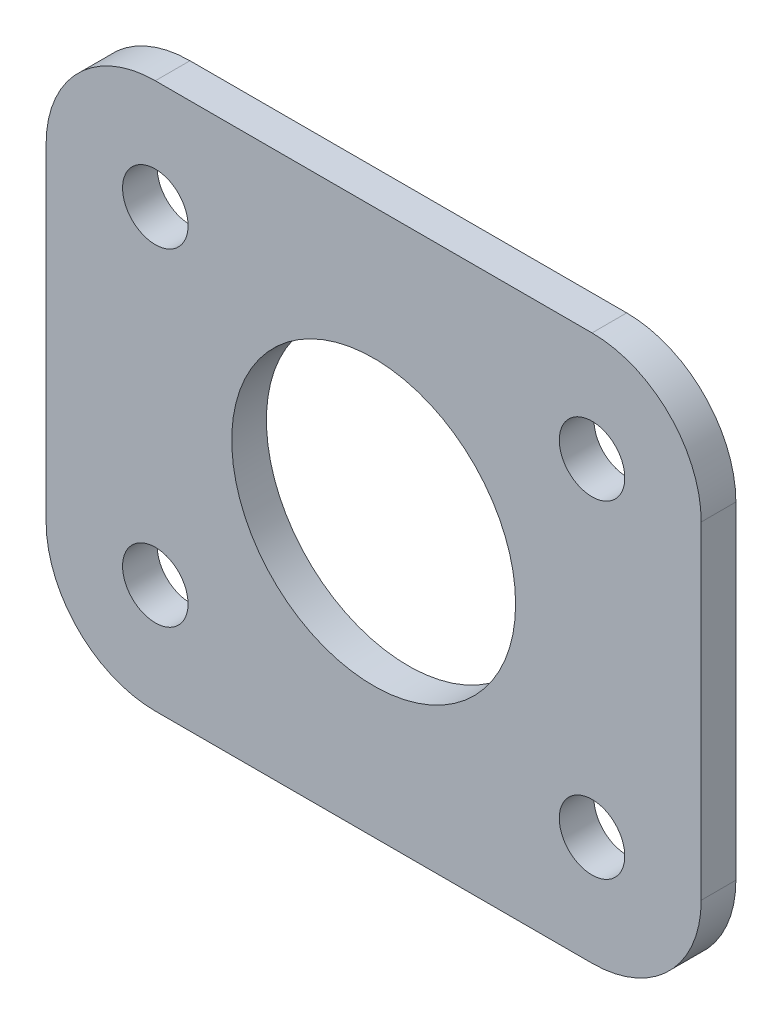
SolidWorks part; units mm, degrees
material "6061 Alloy"
ref_plane "Front Plane" through (0, 0, 0) normal (0, 0, 1) x (1, 0, 0)
ref_plane "Top Plane" through (0, 0, 0) normal (0, 1, 0) x (1, 0, 0)
ref_plane "Right Plane" through (0, 0, 0) normal (1, 0, 0) x (0, 0, -1)
sketch "Sketch1" plane through (0, 0, 0) normal (0, 0, 1) x (1, 0, 0)
  line L0 (0, 0) -> (0, 25)
  line L1 (0, 25) -> (30, 25)
  line L2 (30, 25) -> (30, 0)
  line L6 (0, 0) -> (30, 0)
  line L7 (5, 25) -> (5, 0) construction
  line L8 (0, 0) -> (5, 0) construction
  line L9 (5, 20) -> (5, 25) construction
  line L10 (15, 25) -> (15, 12.5) construction
  line L15 (15, 12.5) -> (15, 0) construction
  circle A0 centre (15, 12.5) radius 6.5
  circle A1 centre (5, 20) radius 1.5
  circle A2 centre (5, 5) radius 1.5
  circle A5 centre (25, 5) radius 1.5
  circle A6 centre (25, 20) radius 1.5
  circle A8 centre (15, 12.5) radius 7.5 construction
  dimension "D5" = 13
  dimension "D7" = 3
  dimension "D4" = 15
  dimension "D1" = 30
  dimension "D2" = 25
  dimension "D3" = 5
  dimension "D6" = 5
  dimension "D8" = 5
extrude "Boss-Extrude1" add sketch "Sketch1" along normal blind 1.5875
fillet "Fillet1" radius 5 4 edges at (0, 25, 0.7937) (30, 25, 0.7937) (30, 0, 0.7937) (0, 0, 0.7937)
